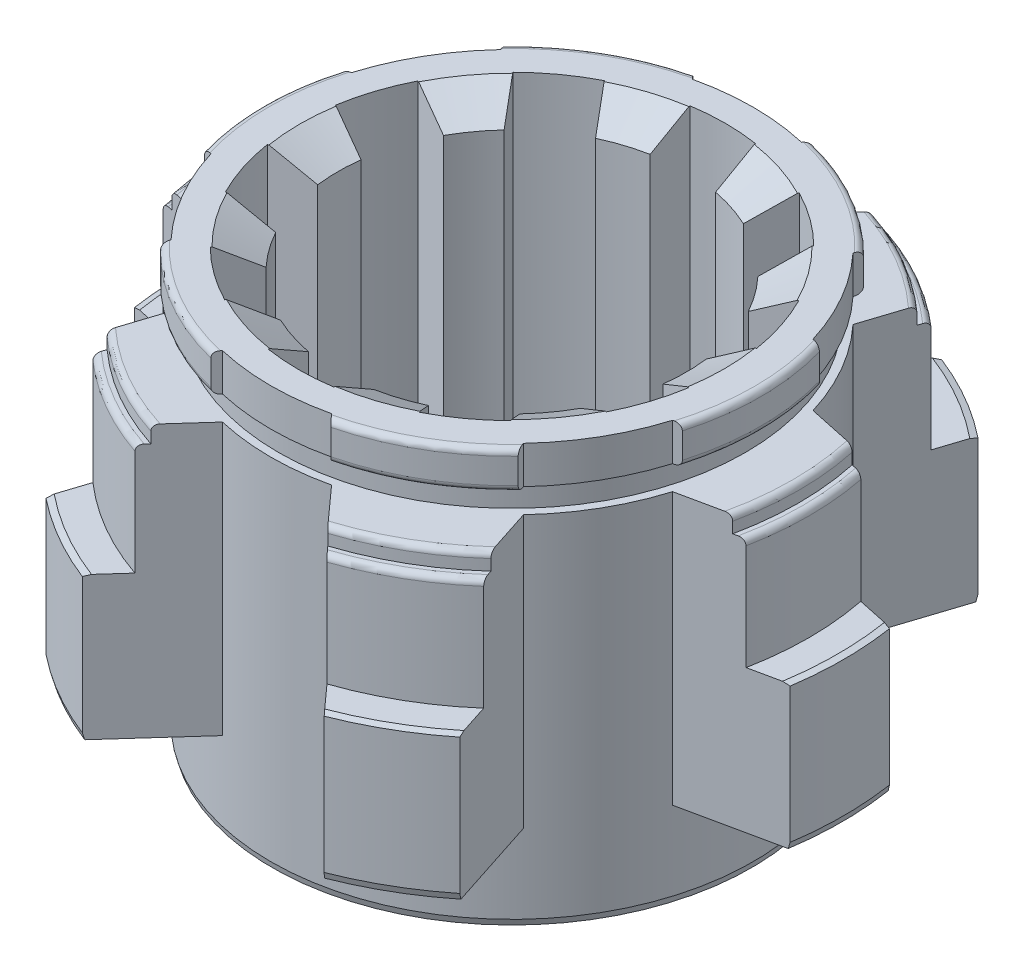
SolidWorks part; units mm, degrees
ref_plane "Plano frontal" through (0, 0, 0) normal (0, 0, 1) x (1, 0, 0)
ref_plane "Plano superior" through (0, 0, 0) normal (0, 1, 0) x (1, 0, 0)
ref_plane "Plano direito" through (0, 0, 0) normal (1, 0, 0) x (0, 0, -1)
sketch "Esboço1" plane through (0, 0, 0) normal (0, 0, 1) x (1, 0, 0)
  line L0 (0, -51.2195) -> (0, 52.8404) construction
  line L1 (14.35, 52.8404) -> (20.5, 52.8404)
  line L2 (20.5, 52.8404) -> (20.5, 49.7404)
  line L3 (20.5, 49.7404) -> (19.25, 49.7404)
  line L4 (19.25, 49.7404) -> (19.25, 47.7404)
  line L5 (19.25, 47.7404) -> (23.65, 47.7404)
  line L6 (23.65, 47.7404) -> (23.65, 46.3404)
  line L7 (23.65, 46.3404) -> (24.5, 46.3404)
  line L8 (24.5, 46.3404) -> (24.5, 37.1404)
  line L9 (24.5, 37.1404) -> (27.35, 37.1404)
  line L10 (27.35, 37.1404) -> (27.35, 25.3404)
  line L11 (27.35, 25.3404) -> (19.9, 25.3404)
  line L12 (19.9, 25.3404) -> (19.9, 18.3404)
  line L13 (19.9, 18.3404) -> (14.35, 18.3404)
  line L14 (14.35, 18.3404) -> (14.35, 52.8404)
  dimension "D1" = 20.5
  dimension "D2" = 14.35
  dimension "D3" = 19.25
  dimension "D4" = 23.65
  dimension "D5" = 24.5
  dimension "D6" = 27.35
  dimension "D7" = 19.9
  dimension "D8" = 7
  dimension "D9" = 11.8
  dimension "D10" = 9.2
  dimension "D11" = 1.4
  dimension "D12" = 2
  dimension "D13" = 3.1
revolve "Revolução1" add sketch "Esboço1" angle 360 about L0
chamfer "Chanfro1" distance 3.15 angle 30 1 edges at (0, 52.8404, -14.35)
chamfer "Chanfro2" distance 3.15 angle 30 1 edges at (0, 18.3404, -14.35)
chamfer "Chanfro3" distance 0.5 angle 15 3 edges at (0, 37.1404, -27.35) (0, 25.3404, -27.35) (0, 18.3404, -19.9)
fillet "Filete1" radius 0.5 4 edges at (0, 47.7404, -23.65) (0, 49.7404, -20.5) (0, 52.8404, -20.5) (0, 46.3404, -24.5)
sketch "Esboço2" plane through (0, 18.3404, 0) normal (0, -1, 0) x (1, 0, 0)
  line L0 (-4.5, -19.3845) -> (-10.8634, -26.4518)
  line L1 (0, 0) -> (0, -19.9) construction
  line L2 (4.5, -19.3845) -> (10.8634, -26.4518)
  line L3 (-19.0375, -5.7952) -> (-28.3397, -3.8179)
  line L4 (-14.5375, -13.5894) -> (-17.4762, -22.6339)
  line L5 (-14.5375, 13.5894) -> (-17.4762, 22.6339)
  line L6 (-19.0375, 5.7952) -> (-28.3397, 3.8179)
  line L7 (4.5, 19.3845) -> (10.8634, 26.4518)
  line L8 (-4.5, 19.3845) -> (-10.8634, 26.4518)
  line L9 (19.0375, 5.7952) -> (28.3397, 3.8179)
  line L10 (14.5375, 13.5894) -> (17.4762, 22.6339)
  line L11 (14.5375, -13.5894) -> (17.4762, -22.6339)
  line L12 (19.0375, -5.7952) -> (28.3397, -3.8179)
  arc A0 (-10.8634, -26.4518) -> (10.8634, -26.4518) centre (0, -1.1981) ccw
  arc A1 (-4.5, -19.3845) -> (4.5, -19.3845) centre (0, 0) ccw
  arc A2 (-28.3397, -3.8179) -> (-17.4762, -22.6339) centre (-1.0376, -0.599) ccw
  arc A3 (-19.0375, -5.7952) -> (-14.5375, -13.5894) centre (0, 0) ccw
  arc A4 (-17.4762, 22.6339) -> (-28.3397, 3.8179) centre (-1.0376, 0.599) ccw
  arc A5 (-14.5375, 13.5894) -> (-19.0375, 5.7952) centre (0, 0) ccw
  arc A6 (10.8634, 26.4518) -> (-10.8634, 26.4518) centre (0, 1.1981) ccw
  arc A7 (4.5, 19.3845) -> (-4.5, 19.3845) centre (0, 0) ccw
  arc A8 (28.3397, 3.8179) -> (17.4762, 22.6339) centre (1.0376, 0.599) ccw
  arc A9 (19.0375, 5.7952) -> (14.5375, 13.5894) centre (0, 0) ccw
  arc A10 (17.4762, -22.6339) -> (28.3397, -3.8179) centre (1.0376, -0.599) ccw
  arc A11 (14.5375, -13.5894) -> (19.0375, -5.7952) centre (0, 0) ccw
  dimension "D1" = 6
extrude "Corte-extrusão1" cut sketch "Esboço2" against normal through all
sketch "Esboço3" plane through (0, 18.3404, 0) normal (0, -1, 0) x (1, 0, 0)
  line L0 (-2.7, -17.3917) -> (-2.7, -13.3118)
  line L1 (0, 0) -> (0, -17.6) construction
  line L2 (-2.7, -13.3118) -> (2.7, -13.3118)
  line L3 (2.7, -13.3118) -> (2.7, -17.3917)
  line L4 (-12.4069, -12.4831) -> (-10.0088, -9.1824)
  line L5 (-10.0088, -9.1824) -> (-5.6401, -12.3565)
  line L6 (-5.6401, -12.3565) -> (-8.0382, -15.6572)
  line L7 (-17.3748, -2.8065) -> (-13.4946, -1.5457)
  line L8 (-13.4946, -1.5457) -> (-11.8259, -6.6814)
  line L9 (-11.8259, -6.6814) -> (-15.7061, -7.9422)
  line L10 (-15.7061, 7.9422) -> (-11.8259, 6.6814)
  line L11 (-11.8259, 6.6814) -> (-13.4946, 1.5457)
  line L12 (-13.4946, 1.5457) -> (-17.3748, 2.8065)
  line L13 (-8.0382, 15.6572) -> (-5.6401, 12.3565)
  line L14 (-5.6401, 12.3565) -> (-10.0088, 9.1824)
  line L15 (-10.0088, 9.1824) -> (-12.4069, 12.4831)
  line L16 (2.7, 17.3917) -> (2.7, 13.3118)
  line L17 (2.7, 13.3118) -> (-2.7, 13.3118)
  line L18 (-2.7, 13.3118) -> (-2.7, 17.3917)
  line L19 (12.4069, 12.4831) -> (10.0088, 9.1824)
  line L20 (10.0088, 9.1824) -> (5.6401, 12.3565)
  line L21 (5.6401, 12.3565) -> (8.0382, 15.6572)
  line L22 (17.3748, 2.8065) -> (13.4946, 1.5457)
  line L23 (13.4946, 1.5457) -> (11.8259, 6.6814)
  line L24 (11.8259, 6.6814) -> (15.7061, 7.9422)
  line L25 (15.7061, -7.9422) -> (11.8259, -6.6814)
  line L26 (11.8259, -6.6814) -> (13.4946, -1.5457)
  line L27 (13.4946, -1.5457) -> (17.3748, -2.8065)
  line L28 (8.0382, -15.6572) -> (5.6401, -12.3565)
  line L29 (5.6401, -12.3565) -> (10.0088, -9.1824)
  line L30 (10.0088, -9.1824) -> (12.4069, -12.4831)
  arc A0 (-12.4069, -12.4831) -> (-8.0382, -15.6572) centre (0, 0) ccw
  arc A1 (-2.7, -17.3917) -> (2.7, -17.3917) centre (0, 0) ccw
  arc A2 (-17.3748, -2.8065) -> (-15.7061, -7.9422) centre (0, 0) ccw
  arc A3 (-15.7061, 7.9422) -> (-17.3748, 2.8065) centre (0, 0) ccw
  arc A4 (-8.0382, 15.6572) -> (-12.4069, 12.4831) centre (0, 0) ccw
  arc A5 (2.7, 17.3917) -> (-2.7, 17.3917) centre (0, 0) ccw
  arc A6 (12.4069, 12.4831) -> (8.0382, 15.6572) centre (0, 0) ccw
  arc A7 (17.3748, 2.8065) -> (15.7061, 7.9422) centre (0, 0) ccw
  arc A8 (15.7061, -7.9422) -> (17.3748, -2.8065) centre (0, 0) ccw
  arc A9 (8.0382, -15.6572) -> (12.4069, -12.4831) centre (0, 0) ccw
  dimension "D1" = 10
extrude "Corte-extrusão2" cut sketch "Esboço3" against normal through all
